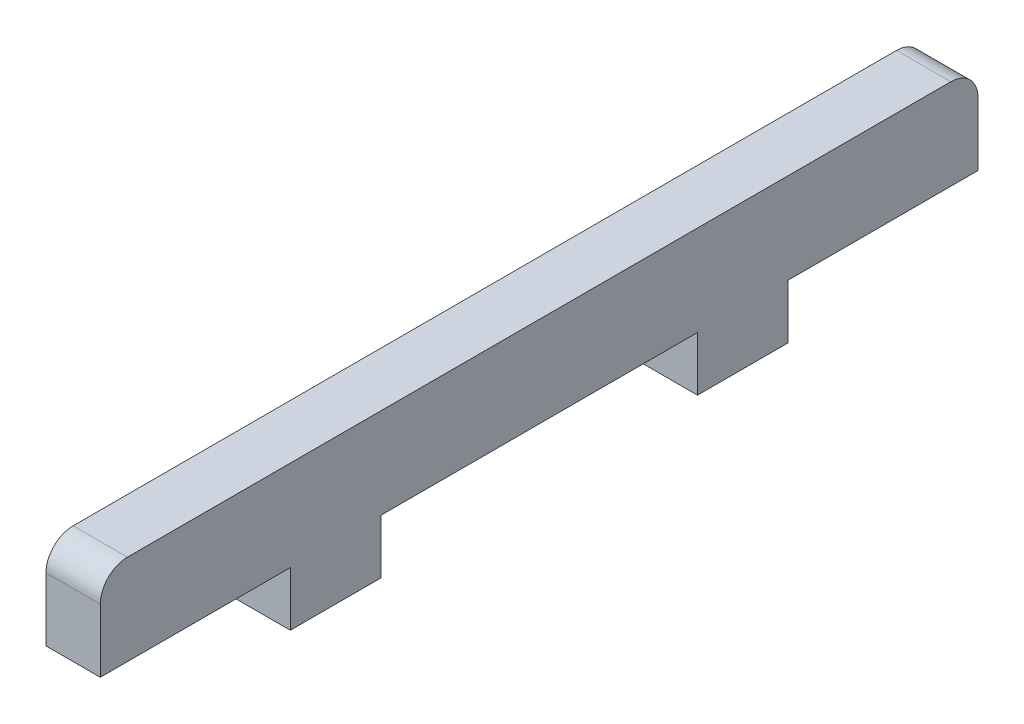
SolidWorks part; units mm, degrees
ref_plane "Front Plane" through (0, 0, 0) normal (0, 0, 1) x (1, 0, 0)
ref_plane "Top Plane" through (0, 0, 0) normal (0, 1, 0) x (1, 0, 0)
ref_plane "Right Plane" through (0, 0, 0) normal (1, 0, 0) x (0, 0, -1)
sketch "Sketch1" plane through (0, 0, 0) normal (1, 0, 0) x (0, 0, -1)
  line L0 (-394.6512, 227.9047) -> (-265.9159, 227.9047) construction
  line L1 (-390.6512, 243.9047) -> (-293.6512, 243.9047)
  line L2 (-390.6512, 243.9047) -> (-390.6512, 233.9047)
  line L3 (-390.6512, 233.9047) -> (-293.6512, 233.9047) construction
  line L4 (-293.6512, 243.9047) -> (-293.6512, 233.9047)
  line L5 (-369.6512, 233.9047) -> (-369.6512, 227.9047)
  line L6 (-369.6512, 227.9047) -> (-359.6512, 227.9047)
  line L7 (-359.6512, 227.9047) -> (-359.6512, 233.9047)
  line L8 (-324.6512, 233.9047) -> (-324.6512, 227.9047)
  line L9 (-324.6512, 227.9047) -> (-314.6512, 227.9047)
  line L10 (-314.6512, 227.9047) -> (-314.6512, 233.9047)
  line L11 (-390.6512, 233.9047) -> (-369.6512, 233.9047)
  line L12 (-359.6512, 233.9047) -> (-324.6512, 233.9047)
  line L13 (-314.6512, 233.9047) -> (-293.6512, 233.9047)
  dimension "D1" = 10
  dimension "D2" = 6
  dimension "D3" = 35
  dimension "D4" = 10
  dimension "D5" = 21
  dimension "D6" = 21
extrude "Boss-Extrude1" add sketch "Sketch1" along normal blind 6
fillet "Fillet1" radius 3 2 edges at (3, 243.9047, 293.6512) (3, 243.9047, 390.6512)
